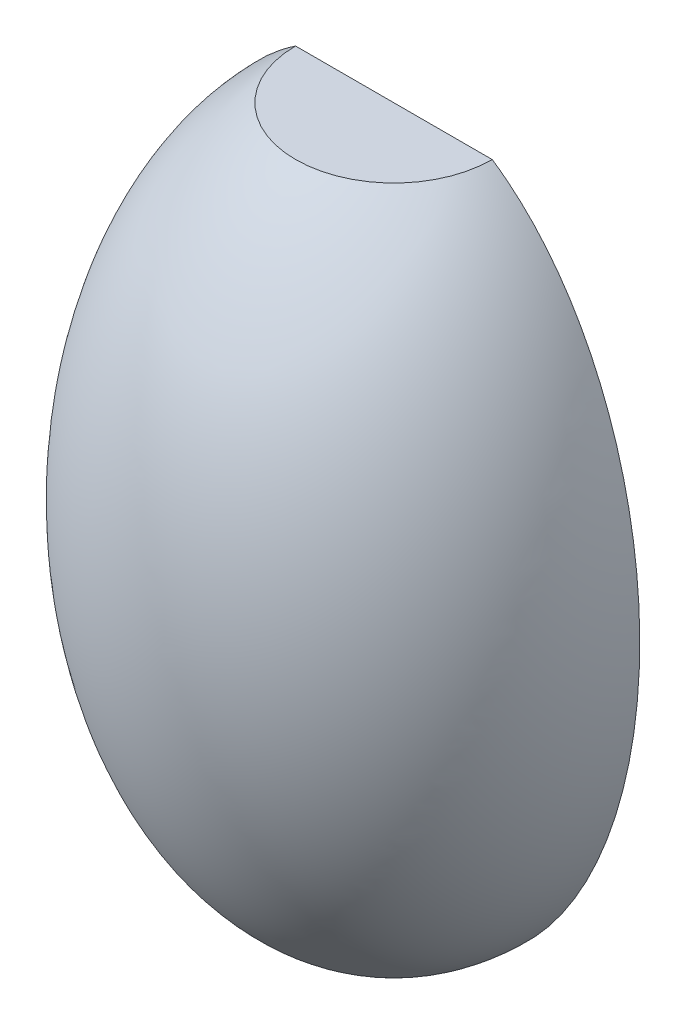
SolidWorks part; units mm, degrees
ref_plane "Alzado" through (0, 0, 0) normal (0, 0, 1) x (1, 0, 0)
ref_plane "Planta" through (0, 0, 0) normal (0, 1, 0) x (1, 0, 0)
ref_plane "Vista lateral" through (0, 0, 0) normal (1, 0, 0) x (0, 0, -1)
sketch "Croquis1" plane through (0, 0, 0) normal (0, 0, 1) x (1, 0, 0)
  line L0 (0, 35) -> (10, 35)
  line L2 (0, -35) -> (10, -35)
  line L3 (0, 0) -> (0, 35)
  line L4 (0, 0) -> (0, -35)
  ellipse E1 centre (0, 0) end of major axis (0, 38.1881) minor radius 25 (10, -35) -> (10, 35) ccw
  dimension "D1" = 70
revolve "Revolución1" add sketch "Croquis1" angle 360 about L3
shell "Vaciado1" thickness 2
sketch "Croquis2" plane through (0, 35, 0) normal (0, 1, 0) x (1, 0, 0)
  circle A0 centre (0, 0) radius 10
extrude "Saliente-Extruir1" add sketch "Croquis2" against normal blind 2
sketch "Croquis3" plane through (0, -35, 0) normal (0, -1, 0) x (1, 0, 0)
  circle A0 centre (0, 0) radius 10
extrude "Saliente-Extruir2" add sketch "Croquis3" against normal blind 2
sketch "Croquis4" plane through (0, 0, 0) normal (0, 0, 1) x (1, 0, 0)
  line L1 (-37.4275, 39.2502) -> (43.3942, 39.2502)
  line L2 (-37.4275, 39.2502) -> (-37.4275, -40.7498)
  line L3 (-37.4275, -40.7498) -> (43.3942, -40.7498)
  line L4 (43.3942, 39.2502) -> (43.3942, -40.7498)
  dimension "D1" = 80
extrude "Cortar-Extruir1" cut sketch "Croquis4" against normal blind 50
